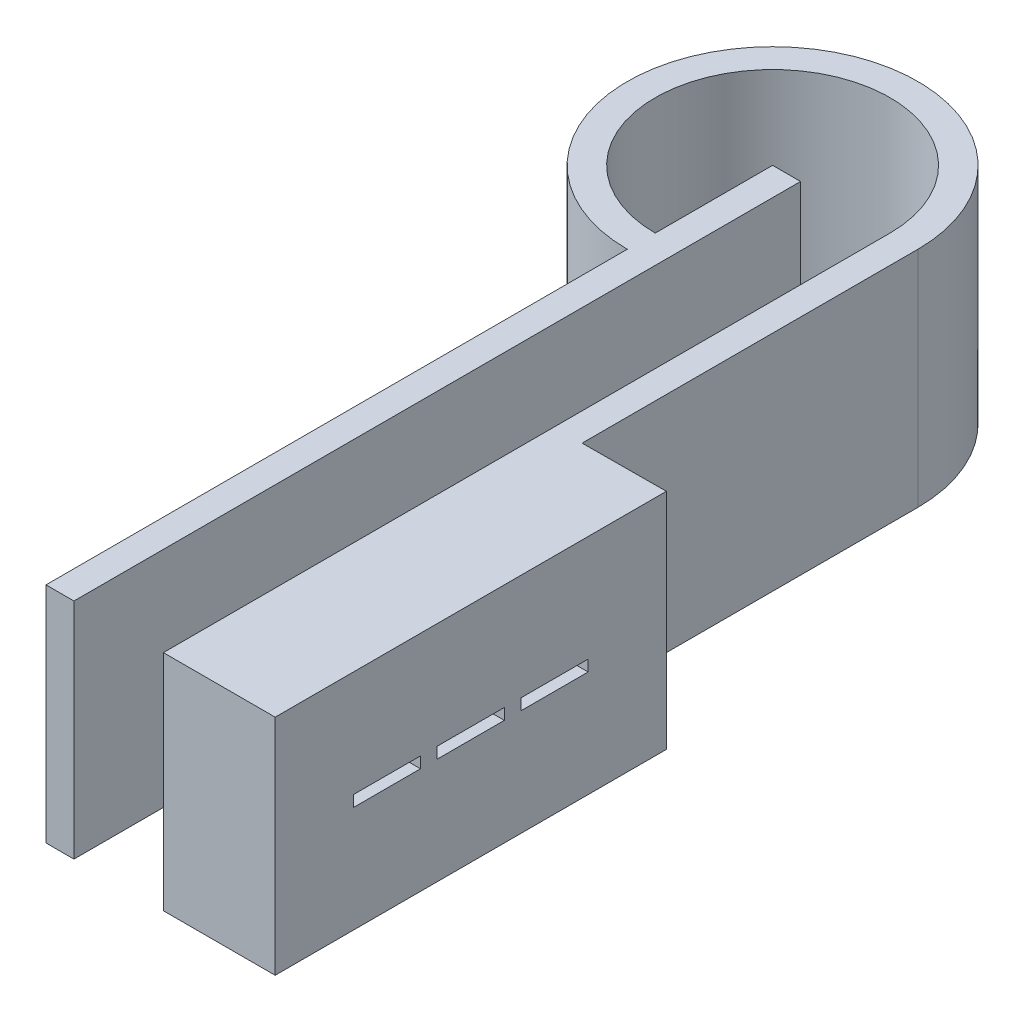
SolidWorks part; units mm, degrees
ref_plane "Front Plane" through (0, 0, 0) normal (0, 0, 1) x (1, 0, 0)
ref_plane "Top Plane" through (0, 0, 0) normal (0, 1, 0) x (1, 0, 0)
ref_plane "Right Plane" through (0, 0, 0) normal (1, 0, 0) x (0, 0, -1)
sketch "Sketch1" plane through (0, 0, 0) normal (0, 1, 0) x (1, 0, 0)
  line L0 (-30.8012, 22.7489) -> (-30.8012, -7.2931)
  line L1 (-43.8012, 22.7489) -> (-41.3012, 22.7489)
  line L2 (-43.8012, 22.7489) -> (-43.8012, -37.2511)
  line L3 (-43.8012, -37.2511) -> (-41.3012, -37.2511)
  line L4 (-41.3012, 22.7489) -> (-41.3012, -37.2511)
  line L5 (-33.3012, 22.7489) -> (-23.3012, 22.7489)
  line L6 (-33.3012, 22.7489) -> (-33.3012, -37.2511)
  line L7 (-33.3012, -37.2511) -> (-23.3012, -37.2511)
  line L8 (-23.3012, 22.7489) -> (-23.3012, -37.2511)
  line L9 (-30.8012, -7.2931) -> (-23.3012, -7.2511)
  arc A0 (-30.8012, 22.7489) -> (-43.8012, 9.7489) centre (-43.8012, 22.7489) ccw
  arc A1 (-33.3012, 22.7489) -> (-43.8012, 12.2489) centre (-43.8012, 22.7489) ccw
  point P8 (-42.5512, -37.2511)
  point P9 (-33.3012, -7.2511)
  dimension "D1" = 60
  dimension "D2" = 60
  dimension "D3" = 8
  dimension "D4" = 10
  dimension "D5" = 2.5
  dimension "D6" = 2.5
  dimension "D7" = 2.5
extrude "Boss-Extrude1" add sketch "Sketch1" along normal blind 20
sketch "Sketch2" plane through (-33.3012, 0, 0) normal (-1, 0, 0) x (0, 0, 1)
  line L0 (-9.7489, 20) -> (37.2511, 20) construction
  line L5 (37.2511, 20) -> (37.2511, 0) construction
  circle A0 centre (24.7511, 10) radius 2.6
  circle A1 centre (17.2511, 10) radius 4
  circle A2 centre (32.2511, 10) radius 4
  dimension "D5" = 10
  dimension "D7" = 7.5
  dimension "D1" = 10
  dimension "D2" = 7.5
  dimension "D6" = 10
  dimension "D8" = 12.5
extrude "Cut-Extrude2" cut sketch "Sketch2" against normal blind 8 contours A1 | A2
sketch "Sketch3" plane through (-23.3012, 0, 0) normal (1, 0, 0) x (0, 0, -1)
  line L0 (-27.7511, 10.5) -> (-21.7511, 9.5)
  line L1 (-27.7511, 9.5) -> (-21.7511, 10.5)
  line L2 (-20.2511, 10.5) -> (-14.2511, 9.5)
  line L3 (-14.2511, 10.5) -> (-20.2511, 10.5)
  line L4 (-14.2511, 10.5) -> (-14.2511, 9.5)
  line L5 (-14.2511, 9.5) -> (-20.2511, 9.5)
  line L6 (-20.2511, 10.5) -> (-20.2511, 9.5)
  line L7 (-21.7511, 10.5) -> (-27.7511, 10.5)
  line L8 (-21.7511, 10.5) -> (-21.7511, 9.5)
  line L9 (-21.7511, 9.5) -> (-27.7511, 9.5)
  line L10 (-27.7511, 10.5) -> (-27.7511, 9.5)
  line L11 (-20.2511, 9.5) -> (-14.2511, 10.5)
  line L12 (-37.2511, 20) -> (-37.2511, 0) construction
  line L13 (-7.2511, 20) -> (-37.2511, 20) construction
  line L14 (-35.2511, 10.5) -> (-29.2511, 9.5)
  line L15 (-29.2511, 10.5) -> (-35.2511, 10.5)
  line L16 (-29.2511, 10.5) -> (-29.2511, 9.5)
  line L17 (-29.2511, 9.5) -> (-35.2511, 9.5)
  line L18 (-35.2511, 10.5) -> (-35.2511, 9.5)
  line L19 (-35.2511, 9.5) -> (-29.2511, 10.5)
  line L20 (-7.2511, 20) -> (-37.2511, 20) construction
  point P2 (-24.7511, 10)
  point P3 (-17.2511, 10)
  point P5 (-32.2511, 10)
  dimension "D1" = 6
  dimension "D2" = 6
  dimension "D3" = 12.5
  dimension "D4" = 7.5
  dimension "D5" = 10
  dimension "D6" = 10
  dimension "D7" = 1
  dimension "D8" = 10
  dimension "D9" = 7.5
  dimension "D10" = 6
  dimension "D11" = 1
extrude "Cut-Extrude4" cut sketch "Sketch3" against normal blind 10 contours L0 L10 L1 | L1 L7 L0 | L8 L1 L0 | L9 L0 L1 | L6 L11 L2 | L11 L2 L4 | L2 L11 L3 | L11 L5 L2 | L19 L14 L16 | L14 L19 L15 | L18 L19 L14 | L19 L17 L14
sketch "Sketch4" plane through (-33.3012, 0, 0) normal (-1, 0, 0) x (0, 0, 1)
  line L0 (37.2511, 20) -> (37.2511, 0) construction
  line L1 (-9.7489, 20) -> (37.2511, 20) construction
  circle A0 centre (24.7511, 10) radius 2.6
  dimension "D1" = 12.5
  dimension "D2" = 10
extrude "Cut-Extrude5" cut sketch "Sketch4" against normal blind 1.5
sketch "Sketch6" plane through (0, 0, 37.2511) normal (0, 0, 1) x (1, 0, 0)
  line L1 (-43.8012, 20) -> (-41.3012, 20)
  line L2 (-43.8012, 20) -> (-43.8012, 0)
  line L3 (-43.8012, 0) -> (-41.3012, 0)
  line L4 (-41.3012, 20) -> (-41.3012, 0)
  line L5 (-33.3012, 0) -> (-23.3012, 0)
  line L6 (-33.3012, 0) -> (-33.3012, 20)
  line L7 (-33.3012, 20) -> (-23.3012, 20)
  line L8 (-23.3012, 0) -> (-23.3012, 20)
extrude "Boss-Extrude3" add sketch "Sketch6" along normal blind 5
